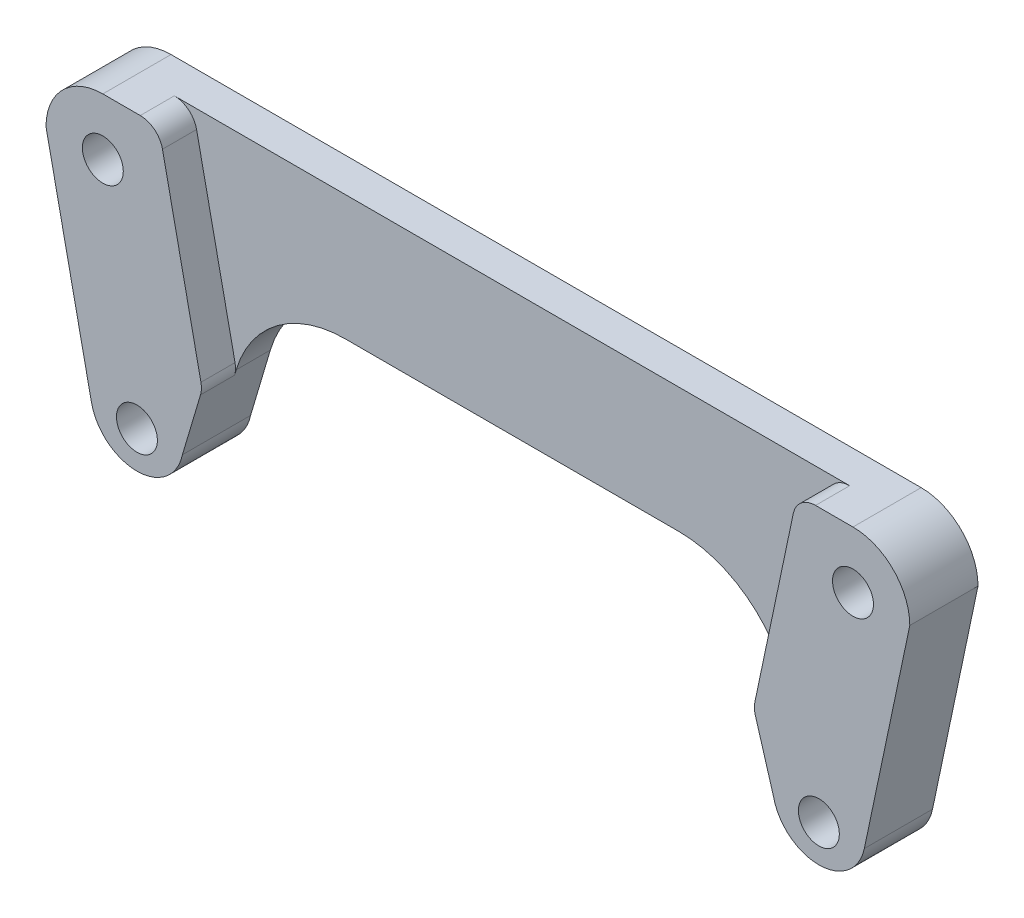
SolidWorks part; units mm, degrees
ref_plane "正面" through (0, 0, 0) normal (0, 0, 1) x (1, 0, 0)
ref_plane "平面" through (0, 0, 0) normal (0, 1, 0) x (1, 0, 0)
ref_plane "右側面" through (0, 0, 0) normal (1, 0, 0) x (0, 0, -1)
sketch "ｽｹｯﾁ1" plane through (0, 0, 0) normal (0, 0, 1) x (1, 0, 0)
  line L0 (-35.8008, -0.4332) -> (-35.8008, 59.6849) construction
  line L1 (-68.8008, 45.1897) -> (-2.8008, 45.1897)
  line L2 (-73.8008, 40.1897) -> (-69.8008, 21.1897)
  line L3 (-11.5375, 27.0369) -> (-9.8008, 21.1897)
  line L4 (2.1992, 40.1897) -> (-1.8008, 21.1897)
  line L5 (-68.8008, 40.1897) -> (-2.8008, 40.1897) construction
  line L6 (-65.8008, 21.1897) -> (-5.8008, 21.1897) construction
  line L7 (-61.8008, 21.1897) -> (-60.0641, 27.0369)
  line L8 (-21.1236, 34.1897) -> (-50.478, 34.1897)
  line L9 (-65.8008, 21.1897) -> (-77.5031, 21.1897) construction
  line L10 (-68.8008, 40.1897) -> (-83.072, 40.1897) construction
  circle A0 centre (-68.8008, 40.1897) radius 1.8
  circle A1 centre (-65.8008, 21.1897) radius 1.8
  circle A2 centre (-5.8008, 21.1897) radius 1.8
  circle A3 centre (-2.8008, 40.1897) radius 1.8
  arc A4 (-68.8008, 45.1897) -> (-73.8008, 40.1897) centre (-68.8008, 40.1897) ccw
  arc A5 (-69.8008, 21.1897) -> (-61.8008, 21.1897) centre (-65.8008, 22.0319) ccw
  arc A6 (-60.0641, 27.0369) -> (-50.478, 34.1897) centre (-50.478, 24.1897) cw
  arc A7 (-11.5375, 27.0369) -> (-21.1236, 34.1897) centre (-21.1236, 24.1897) ccw
  arc A8 (-2.8008, 45.1897) -> (2.1992, 40.1897) centre (-2.8008, 40.1897) cw
  arc A9 (-1.8008, 21.1897) -> (-9.8008, 21.1897) centre (-5.8008, 22.0319) cw
  point P20 (-35.8008, 45.1897)
  point P21 (-35.8008, 34.1897)
  dimension "D6" = 3.6
  dimension "D12" = 10
  dimension "D1" = 33
  dimension "D2" = 33
  dimension "D3" = 19
  dimension "D4" = 30
  dimension "D5" = 30
  dimension "D7" = 5
  dimension "D8" = 5
  dimension "D9" = 6
  dimension "D10" = 4
  dimension "D11" = 4
extrude "ﾎﾞｽ - 押し出し1" add sketch "ｽｹｯﾁ1" along normal blind 6
sketch "ｽｹｯﾁ2" plane through (0, 0, 6) normal (0, 0, 1) x (1, 0, 0)
  line L0 (-2.8008, 45.1897) -> (-68.8008, 45.1897) construction
  line L1 (-60.0641, 27.0369) -> (-11.5375, 27.0369)
  line L2 (-60.0641, 27.0369) -> (-63.8858, 45.1897)
  line L3 (-63.8858, 45.1897) -> (-7.7159, 45.1897)
  line L4 (-11.5375, 27.0369) -> (-7.7159, 45.1897)
  line L5 (-1.8008, 21.1897) -> (2.1992, 40.1897) construction
  line L6 (-73.8008, 40.1897) -> (-69.8008, 21.1897) construction
extrude "ｶｯﾄ - 押し出し1" cut sketch "ｽｹｯﾁ2" against normal blind 3
fillet "ﾌｨﾚｯﾄ1" radius 2 4 edges at (-11.5375, 27.0369, 4.5) (-60.0641, 27.0369, 4.5) (-7.7159, 45.1897, 4.5) (-63.8858, 45.1897, 4.5)
